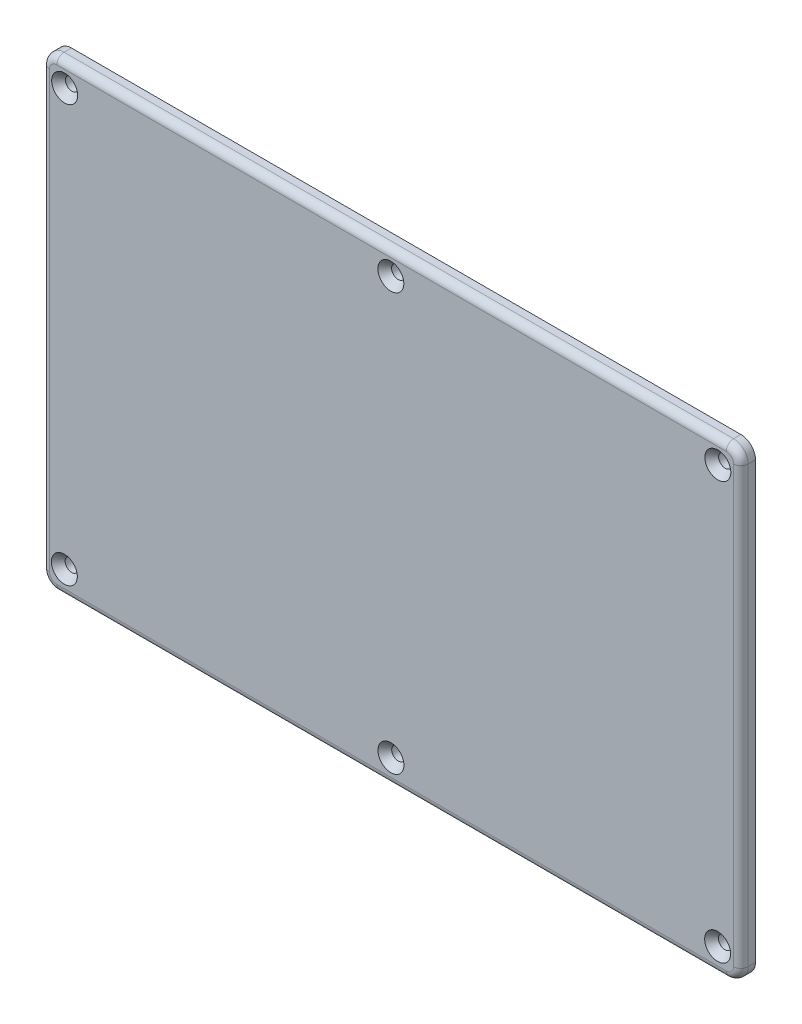
SolidWorks part; units mm, degrees
ref_plane "Front Plane" through (0, 0, 0) normal (0, 0, 1) x (1, 0, 0)
ref_plane "Top Plane" through (0, 0, 0) normal (0, 1, 0) x (1, 0, 0)
ref_plane "Right Plane" through (0, 0, 0) normal (1, 0, 0) x (0, 0, -1)
sketch "Sketch3" plane through (0, 0, 0) normal (0, 0, 1) x (1, 0, 0)
  line L1 (-95.5, 63.5) -> (95.5, 63.5)
  line L2 (-95.5, 63.5) -> (-95.5, -63.5)
  line L3 (-95.5, -63.5) -> (95.5, -63.5)
  line L4 (95.5, 63.5) -> (95.5, -63.5)
  line L5 (-95.5, 63.5) -> (95.5, -63.5) construction
  line L6 (-95.5, -63.5) -> (95.5, 63.5) construction
  point P0 (0, 0)
  dimension "D1" = 191
  dimension "D2" = 127
extrude "Boss-Extrude3" add sketch "Sketch3" along normal blind 4
sketch "Sketch6" plane through (0, 0, 0) normal (0, 0, 1) x (1, 0, 0)
  circle A0 centre (-89.2941, 57.1284) radius 4
  circle A1 centre (89.3018, 57.1284) radius 4
  circle A2 centre (89.3018, -56.8526) radius 4
  circle A4 centre (-89.2941, -56.8526) radius 4
  circle A5 centre (0, -56.8526) radius 4
  circle A6 centre (0, 57.1284) radius 4
  point P4 (90.7579, 58.6667)
  point P7 (90.7579, -56.0823)
  point P8 (90.7579, -58.7963)
  point P9 (0, 0)
  point P10 (89.3018, -56.8526)
  point P11 (0, 0)
  point P12 (0, 0)
  point P15 (-90.716, -58.7963)
  point P16 (89.3018, 57.1284)
  point P17 (0, 0)
  point P18 (-89.2941, 57.1284)
  point P19 (-89.2941, -56.8526)
  point P22 (0, -56.8526)
  point P25 (0, 57.1284)
extrude "Boss-Extrude4" add sketch "Sketch6" along normal blind 0.001
hole_wizard "Hole1" positions "3DSketch6" profile "Sketch11" legacy
sketch3d "3DSketch6"
  point P0 (-89.3586, 57.0956, 4)
  point P2 (-0.1917, 57.1257, 4)
  point P4 (89.2052, 57.1455, 4)
  point P6 (89.1478, -56.882, 4)
  point P8 (-0.1608, -56.8565, 4)
  point P10 (-89.4443, -56.8624, 4)
sketch "Sketch11" plane through (-89.3586, 57.0956, 4) normal (1, 0, 0) x (0, -1, 0)
  line L0 (0, 0) -> (0, 5)
  line L1 (0, 5) -> (1.8, 5)
  line L2 (1.8, 5) -> (1.8, 2.0131)
  line L3 (1.8, 2.0131) -> (3.55, 0)
  line L4 (3.55, 0) -> (0, 0)
  line L5 (0, -6.4453) -> (0, 115.525) construction
  line L6 (-1.8, 2.0131) -> (-3.55, 0) construction
  dimension "Diameter" = 3.6
  dimension "Depth" = 5
  dimension "C-Sink Angle" = 82
  dimension "C-Sink Diameter" = 7.1
fillet "Fillet1" radius 4 4 edges at (95.5, 63.5, 2) (-95.5, 63.5, 2) (-95.5, -63.5, 2) (95.5, -63.5, 2)
fillet "Fillet2" radius 2 8 edges at (-94.3284, -62.3284, 4) (-95.5, 0, 4) (-94.3284, 62.3284, 4) (0, 63.5, 4) (94.3284, 62.3284, 4) (95.5, 0, 4) (94.3284, -62.3284, 4) (0, -63.5, 4)
